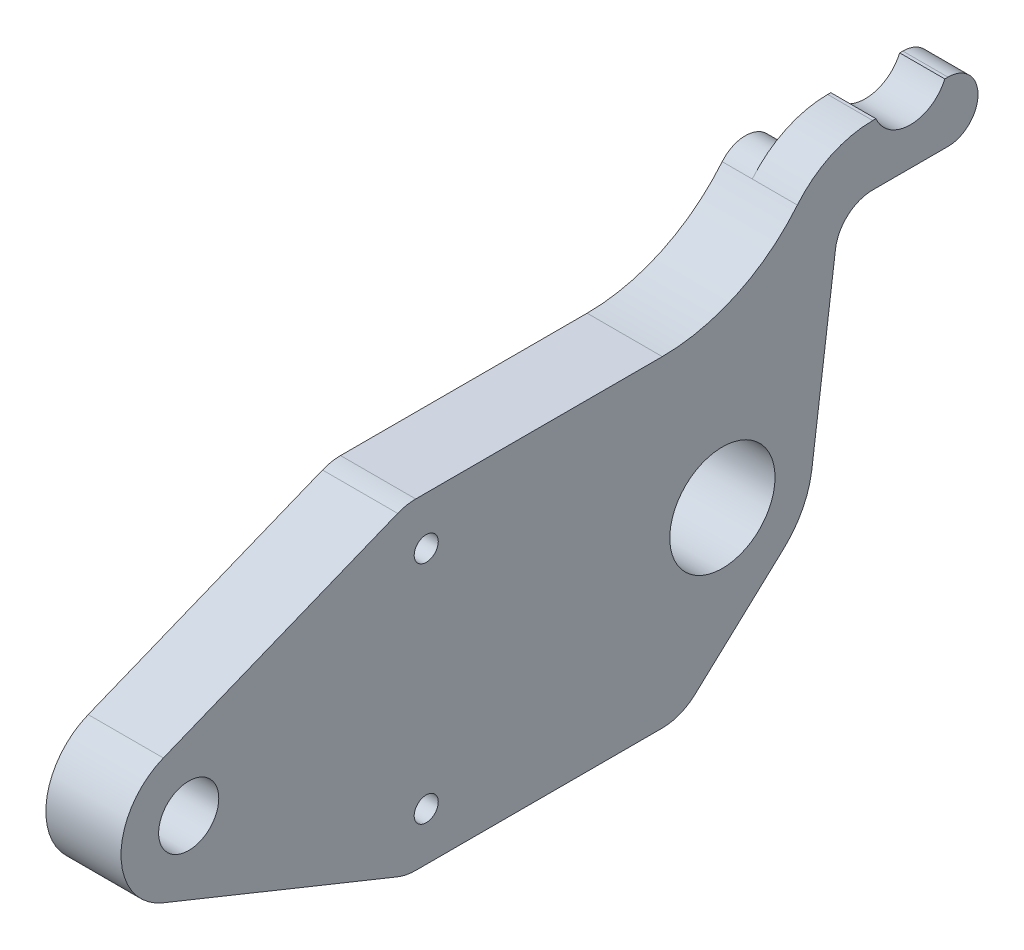
SolidWorks part; units mm, degrees
material "Alliage 1060"
ref_plane "Plan de face" through (0, 0, 0) normal (0, 0, 1) x (1, 0, 0)
ref_plane "Plan de dessus" through (0, 0, 0) normal (0, 1, 0) x (1, 0, 0)
ref_plane "Plan de droite" through (0, 0, 0) normal (1, 0, 0) x (0, 0, -1)
sketch "Esquisse1" plane through (0, 0, 0) normal (0, 0, 1) x (1, 0, 0)
  line L0 (0, 14) -> (0, -14) construction
  line L1 (-2.5, 14) -> (2.5, 14)
  line L2 (-2.5, 14) -> (-2.5, -14)
  line L3 (-2.5, -14) -> (2.5, -14)
  line L4 (2.5, 14) -> (2.5, -14)
  dimension "D1" = 5
  dimension "D2" = 28
extrude "Extrusion1" add sketch "Esquisse1" against normal blind 46
sketch "Esquisse2" plane through (2.5, 0, 0) normal (1, 0, 0) x (0, 0, -1)
  line L0 (4.5, -3.3) -> (40, -3.3) construction
  line L2 (46, -14) -> (46, 14) construction
  line L4 (0, -14) -> (0, 14) construction
  line L6 (46, 14) -> (0, 14) construction
  circle A0 centre (4.5, -3.3) radius 2
  circle A1 centre (40, -3.3) radius 3.5
  dimension "D2" = 4
  dimension "D6" = 7
  dimension "D1" = 2.5
  dimension "D3" = 2.5
  dimension "D4" = 17.3
extrude "Extrusion2" cut sketch "Esquisse2" against normal through all
hole_wizard "Trou taraudé M21" positions "Esquisse10" profile "Esquisse9" tap size "M2" standard "Iso" end condition through all
sketch "Esquisse10" plane through (2.5, 0, 0) normal (1, 0, 0) x (0, 0, -1)
  line L1 (20.3, 4.2) -> (35.3, 4.2)
  line L2 (20.3, 4.2) -> (20.3, -10.8)
  line L3 (20.3, -10.8) -> (35.3, -10.8)
  line L4 (35.3, 4.2) -> (35.3, -10.8)
  line L5 (40, -3.3) -> (35.3, -3.3) construction
  circle A0 centre (40, -3.3) radius 3.5 construction
  point P2 (20.3, 4.2)
  point P100 (20.3, -10.8)
  dimension "D1" = 4.7
  dimension "D2" = 15
sketch "Esquisse9" plane through (2.5, 4.2, -20.3) normal (0, 1, 0) x (0, 0, -1)
  line L0 (0, 0) -> (0, 5)
  line L1 (0, 5) -> (0.8, 5)
  line L2 (0.8, 5) -> (0.8, 0)
  line L5 (0.8, 0) -> (0, 0)
  line L11 (0, -6.35) -> (0, 107.95) construction
  dimension "Diamètre du trou pour taraudage jusqu'au prochain" = 1.6
  dimension "Profondeur du trou pour taraudage jusqu'au prochain" = 5
cosmetic thread "Filetage de perçage12" parameters "D2"=2
cosmetic thread "Filetage de perçage13" parameters "D2"=2
sketch "Esquisse12" plane through (-2.5, 0, 0) normal (-1, 0, 0) x (0, 0, 1)
  line L0 (-46, 14) -> (-50.2087, 14)
  line L1 (-55, 10) -> (-50, 10)
  line L2 (-47.506, 7.6733) -> (-46, -14)
  line L3 (-46, 14) -> (-46, -14)
  line L4 (-54.7913, 14) -> (-55, 14)
  line L5 (-46, 14) -> (0, 14) construction
  arc A0 (-55, 14) -> (-55, 10) centre (-55, 12) ccw
  arc A1 (-50, 10) -> (-47.506, 7.6733) centre (-50, 7.5) cw
  arc A2 (-54.7913, 14) -> (-50.2087, 14) centre (-52.5, 15) ccw
  dimension "D2" = 2.5
  dimension "D4" = 2.5
  dimension "D1" = 4
  dimension "D3" = 2.5
  dimension "D5" = 6.5
  dimension "D6" = 2.5
  dimension "D7" = 2.5
extrude "Boss.-Extru.2" add sketch "Esquisse12" against normal up to surface (5 mm away) up to face at (2.5, 4.2, -21.1)
sketch "Esquisse13" plane through (-2.5, 0, 0) normal (-1, 0, 0) x (0, 0, 1)
  line L0 (0, 14) -> (0, -14) construction
  line L1 (-19.6, -10.8) -> (-36, -10.8) construction
  line L2 (-19.6, -10.8) -> (-19.6, 4.2) construction
  line L3 (-19.6, 4.2) -> (-36, 4.2) construction
  line L4 (-36, -10.8) -> (-36, 4.2) construction
  line L5 (-50.2087, 14) -> (0, 14) construction
  line L6 (-46, -14) -> (0, -14) construction
  line L7 (-47.506, 7.6733) -> (-46, -14)
  line L8 (-46, -14) -> (-36, -14)
  line L9 (-19.6, -14) -> (0, -14)
  line L10 (0, -14) -> (0, -3.3)
  line L11 (0, -3.3) -> (0, 14)
  line L12 (0, 14) -> (-50, 14)
  line L13 (-47.5215, 7.8273) -> (-45.9484, -4.0855)
  line L14 (-44.0685, -7.7099) -> (-38.1699, -13.1519)
  line L15 (-18.4017, -13.7672) -> (-2.8149, -7.4726)
  line L16 (-2.8149, 0.8726) -> (-18.4017, 7.1672)
  line L17 (-19.6, 7.4) -> (-36, 7.4)
  arc A0 (-2.8149, -7.4726) -> (-2.8149, 0.8726) centre (-4.5, -3.3) ccw
  arc A1 (-45.9484, -4.0855) -> (-44.0685, -7.7099) centre (-40, -3.3) ccw
  circle A2 centre (-40, -3.3) radius 3.5 construction
  arc A3 (-19.6, -14) -> (-18.4017, -13.7672) centre (-19.6, -10.8) ccw
  arc A4 (-38.1699, -13.1519) -> (-36, -14) centre (-36, -10.8) ccw
  arc A5 (-18.4017, 7.1672) -> (-19.6, 7.4) centre (-19.6, 4.2) ccw
  arc A6 (-36, 7.4) -> (-44.9858, 11.6362) centre (-36, 19.0485) cw
  arc A7 (-47.506, 7.6733) -> (-50, 10) centre (-50, 7.5) ccw construction
  arc A8 (-47.506, 7.6733) -> (-50, 10) centre (-50, 7.5) ccw
  arc A9 (-44.9858, 11.6362) -> (-50, 14) centre (-50, 7.5) ccw
  arc A10 (-43.5156, 7.9506) -> (-50, 14) centre (-50, 7.5) ccw construction
  circle A11 centre (-36, 4.2) radius 3.2 construction
  circle A12 centre (-19.6, 4.2) radius 3.2 construction
  circle A13 centre (-19.6, -10.8) radius 3.2 construction
  circle A14 centre (-36, -10.8) radius 3.2 construction
  circle A15 centre (-40, -3.3) radius 6 construction
  circle A16 centre (-4.5, -3.3) radius 4.5 construction
  point P7 (-20.3, -10.8)
  point P8 (-20.3, 4.2)
  dimension "D1" = 2.5
  dimension "D2" = 4
  dimension "D3" = 16.4
extrude "Enlèv. mat.-Extru.1" cut sketch "Esquisse13" against normal blind 10
sketch "Esquisse14" plane through (2.5, 0, 0) normal (-1, 0, 0) x (0, 0, 1)
  line L9 (-50, 14) -> (-50.2087, 14)
  line L10 (-54.7913, 14) -> (-55, 14)
  line L11 (-55, 10) -> (-50, 10)
  line L12 (-47.5215, 7.8273) -> (-45.9484, -4.0855)
  line L13 (-44.0685, -7.7099) -> (-38.1699, -13.1519)
  line L14 (-36, -14) -> (-19.6, -14)
  line L15 (-18.4017, -13.7672) -> (-2.8149, -7.4726)
  line L16 (-2.8149, 0.8726) -> (-18.4017, 7.1672)
  line L17 (-19.6, 7.4) -> (-36, 7.4)
  line L18 (-50, 14) -> (-50.2087, 14)
  line L19 (-54.7913, 14) -> (-55, 14)
  line L20 (-55, 10) -> (-50, 10)
  line L21 (-47.5215, 7.8273) -> (-45.9484, -4.0855)
  line L22 (-44.0685, -7.7099) -> (-38.1699, -13.1519)
  line L23 (-36, -14) -> (-19.6, -14)
  line L24 (-18.4017, -13.7672) -> (-2.8149, -7.4726)
  line L25 (-2.8149, 0.8726) -> (-18.4017, 7.1672)
  line L26 (-19.6, 7.4) -> (-36, 7.4)
  arc A0 (-44.9858, 11.6362) -> (-48.0715, 9.0908) centre (-46.5286, 10.3635) ccw
  arc A1 (-44.9858, 11.6362) -> (-36, 7.4) centre (-36, 19.0485) ccw construction
  arc A2 (-47.5215, 7.8273) -> (-50, 10) centre (-50, 7.5) ccw construction
  arc A13 (-44.9858, 11.6362) -> (-36, 7.4) centre (-36, 19.0485) ccw
  arc A14 (-44.9858, 11.6362) -> (-50, 14) centre (-50, 7.5) ccw
  arc A15 (-54.7913, 14) -> (-50.2087, 14) centre (-52.5, 15) ccw
  arc A16 (-55, 14) -> (-55, 10) centre (-55, 12) ccw
  arc A17 (-47.5215, 7.8273) -> (-50, 10) centre (-50, 7.5) ccw
  arc A18 (-45.9484, -4.0855) -> (-44.0685, -7.7099) centre (-40, -3.3) ccw
  arc A19 (-38.1699, -13.1519) -> (-36, -14) centre (-36, -10.8) ccw
  arc A20 (-19.6, -14) -> (-18.4017, -13.7672) centre (-19.6, -10.8) ccw
  arc A21 (-2.8149, -7.4726) -> (-2.8149, 0.8726) centre (-4.5, -3.3) ccw
  arc A22 (-18.4017, 7.1672) -> (-19.6, 7.4) centre (-19.6, 4.2) ccw
  arc A23 (-44.9858, 11.6362) -> (-36, 7.4) centre (-36, 19.0485) ccw
  arc A24 (-44.9858, 11.6362) -> (-50, 14) centre (-50, 7.5) ccw
  arc A25 (-54.7913, 14) -> (-50.2087, 14) centre (-52.5, 15) ccw
  arc A26 (-55, 14) -> (-55, 10) centre (-55, 12) ccw
  arc A27 (-47.5215, 7.8273) -> (-50, 10) centre (-50, 7.5) ccw
  arc A28 (-45.9484, -4.0855) -> (-44.0685, -7.7099) centre (-40, -3.3) ccw
  arc A29 (-38.1699, -13.1519) -> (-36, -14) centre (-36, -10.8) ccw
  arc A30 (-19.6, -14) -> (-18.4017, -13.7672) centre (-19.6, -10.8) ccw
  arc A31 (-2.8149, -7.4726) -> (-2.8149, 0.8726) centre (-4.5, -3.3) ccw
  arc A32 (-18.4017, 7.1672) -> (-19.6, 7.4) centre (-19.6, 4.2) ccw
  line M69 (-50.2087, 14) -> (-50, 14)
  arc M70 (-50, 14) -> (-44.9858, 11.6362) centre (-50, 7.5) cw
  arc M83 (-47.5215, 7.8273) -> (-50, 10) centre (-50, 7.5) ccw
  line M84 (-50, 10) -> (-55, 10)
  arc M85 (-55, 10) -> (-55, 14) centre (-55, 12) cw
  line M86 (-55, 14) -> (-54.7913, 14)
  arc M87 (-54.7913, 14) -> (-50.2087, 14) centre (-52.5, 15) ccw
  dimension "D1" = 0
extrude "Enlèv. mat.-Extru.2" cut sketch "Esquisse14" along normal through all from offset 3 contours A0 M70 M83 M84 M85 M86 M87 M69
